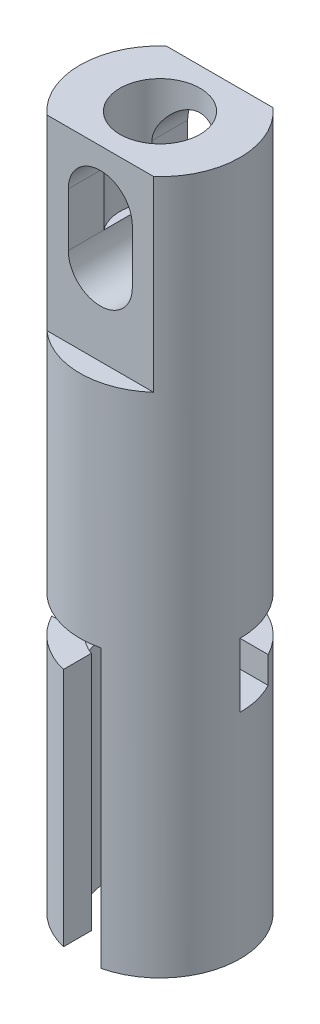
SolidWorks part; units mm, degrees
material "AISI 304"
ref_plane "Front Plane" through (0, 0, 0) normal (0, 0, 1) x (1, 0, 0)
ref_plane "Top Plane" through (0, 0, 0) normal (0, 1, 0) x (1, 0, 0)
ref_plane "Right Plane" through (0, 0, 0) normal (1, 0, 0) x (0, 0, -1)
sketch "Sketch1" plane through (0, 0, 0) normal (0, 1, 0) x (1, 0, 0)
  circle A0 centre (0, 0) radius 15
  dimension "D1" = 30
extrude "Boss-Extrude1" add sketch "Sketch1" along normal mid plane 150
sketch "Sketch2" plane through (0, -75, 0) normal (0, -1, 0) x (1, 0, 0)
  line L0 (0, 15) -> (0, -15) construction
  line L1 (3.5, 15) -> (3.5, -15)
  line L2 (-3.5, 15) -> (-3.5, -15)
  circle A0 centre (0, 0) radius 15 construction
  arc A1 (3.5, 15) -> (-3.5, 15) centre (0, 15) ccw
  arc A2 (-3.5, -15) -> (3.5, -15) centre (0, -15) ccw
  point P6 (0, 0)
  dimension "D1" = 3.5
extrude "Cut-Extrude1" cut sketch "Sketch2" against normal blind 52
ref_plane "Plane1" through (0, -26.5, 0) normal (0, 1, 0) x (1, 0, 0)
sketch "Sketch3" plane through (0, -26.5, 0) normal (0, 1, 0) x (1, 0, 0)
  line L1 (-14.9801, 0) -> (-15.3281, -9.9939)
  line L2 (0, -7) -> (-0.348, -16.9939)
  line L3 (15, 0) -> (0, 7)
  line L4 (15, 0) -> (15.348, 9.9939)
  line L5 (0, 7) -> (0.348, 16.9939)
  line L6 (15.348, 9.9939) -> (0.348, 16.9939)
  line L7 (-15.3281, -9.9939) -> (-0.348, -16.9939)
  line L8 (-14.9801, 0) -> (0, -7)
  circle A0 centre (0, 0) radius 15 construction
  point P0 (0, -7)
  point P5 (-14.9801, 0)
  dimension "D1" = 7
  dimension "D2" = 7
  dimension "D3" = 10
extrude "Cut-Extrude2" cut sketch "Sketch3" against normal mid plane 7
ref_plane "Plane2" through (0, -35, 0) normal (0, 1, 0) x (1, 0, 0)
sketch "Sketch9" plane through (0, -75, 0) normal (0, -1, 0) x (1, 0, 0)
  circle A0 centre (0, 0) radius 10
  dimension "D1" = 20
extrude "Cut-Extrude12" cut sketch "Sketch9" against normal blind 70
ref_plane "Plane5" through (15, 0, 0) normal (1, 0, 0) x (0, 0, -1)
sketch "Sketch17" plane through (15, 0, 0) normal (1, 0, 0) x (0, 0, -1)
  line L0 (0, -23) -> (0, -35)
  line L1 (0, -23) -> (7, -23)
  line L2 (0, -35) -> (7, -35)
  line L3 (7, -23) -> (7, -35)
  line L4 (16.5, -35) -> (-16.5, -35) construction
  dimension "D1" = 7
extrude "Cut-Extrude19" cut sketch "Sketch17" against normal blind 15
ref_plane "Plane6" through (-15, 0, 0) normal (1, 0, 0) x (0, 0, -1)
ref_plane "Plane7" through (-15, 0, 0) normal (-1, 0, 0) x (0, 0, 1)
sketch "Sketch19" plane through (-15, 0, 0) normal (-1, 0, 0) x (0, 0, 1)
  line L0 (0, -23) -> (0, -35)
  line L1 (0, -23) -> (7, -23)
  line L2 (0, -35) -> (7, -35)
  line L3 (7, -23) -> (7, -35)
  line L4 (2.4722, -23) -> (0, -23) construction
  line L5 (16.5, -35) -> (-16.5, -35) construction
  dimension "D1" = 7
extrude "Cut-Extrude20" cut sketch "Sketch19" against normal blind 15
sketch "Sketch20" plane through (0, 75, 0) normal (0, 1, 0) x (1, 0, 0)
  circle A0 centre (0, 0) radius 7.5
  dimension "D1" = 15
extrude "Cut-Extrude21" cut sketch "Sketch20" against normal blind 40
sketch "Sketch21" plane through (0, 75, 0) normal (0, 1, 0) x (1, 0, 0)
  line L1 (-10, 11.1803) -> (10, 11.1803)
  line L2 (-10, 11.1803) -> (-10, 18.8197)
  line L3 (-10, 18.8197) -> (10, 18.8197)
  line L4 (10, 11.1803) -> (10, 18.8197)
  line L5 (-10, 11.1803) -> (10, 18.8197) construction
  line L6 (-10, 18.8197) -> (10, 11.1803) construction
  line L7 (10, -11.1803) -> (10, -18.8197)
  line L8 (-10, -11.1803) -> (-10, -18.8197)
  line L9 (-10, -18.8197) -> (10, -18.8197)
  line L10 (-10, -18.8197) -> (10, -11.1803) construction
  line L11 (-10, -11.1803) -> (10, -18.8197) construction
  line L12 (-10, -11.1803) -> (10, -11.1803)
  circle A0 centre (0, 0) radius 15 construction
  point P0 (0, 15)
  point P12 (0, 0)
  dimension "D1" = 20
extrude "Cut-Extrude25" cut sketch "Sketch21" against normal blind 55 and the other way through all
sketch "Sketch24" plane through (0, 75, 0) normal (0, 1, 0) x (1, 0, 0)
  circle A0 centre (0, 0) radius 15
  dimension "D1" = 30
extrude "Cut-Extrude28" cut sketch "Sketch24" against normal blind 10 and the other way through all
sketch "Sketch25" plane through (0, 65, 0) normal (0, 1, 0) x (1, 0, 0)
  circle A0 centre (0, 0) radius 15
  dimension "D1" = 30
extrude "Cut-Extrude29" cut sketch "Sketch25" against normal blind 10
sketch "Sketch26" plane through (0, 0, 11.1803) normal (0, 0, 1) x (1, 0, 0)
  line L0 (10, 55) -> (-10, 55) construction
  line L1 (0, 45) -> (0, 35) construction
  line L2 (6, 45) -> (6, 35)
  line L3 (-6, 45) -> (-6, 35)
  arc A0 (6, 45) -> (-6, 45) centre (0, 45) ccw
  arc A1 (-6, 35) -> (6, 35) centre (0, 35) ccw
  point P0 (0, 40)
  point P6 (0, 40)
  dimension "D3" = 6
  dimension "D1" = 15
  dimension "D2" = 10
extrude "Cut-Extrude30" cut sketch "Sketch26" against normal through all both and the other way through all
